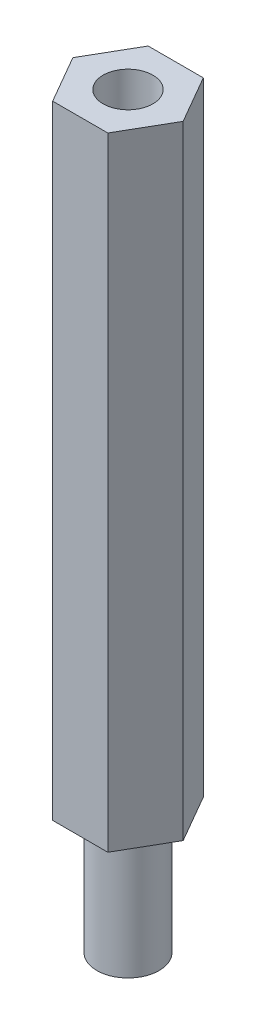
SolidWorks part; units mm, degrees
other "Markup1"
sketch "Sketch2" plane through (2.6558, 40, 2.3) normal (0.3825, 0.9065, 0.1787) x (0.7461, -0.1889, -0.6385)
ref_plane "Front Plane" through (0, 0, 0) normal (0, 0, 1) x (1, 0, 0)
ref_plane "Top Plane" through (0, 0, 0) normal (0, 1, 0) x (1, 0, 0)
ref_plane "Right Plane" through (0, 0, 0) normal (1, 0, 0) x (0, 0, -1)
sketch "Sketch1" plane through (0, 0, 0) normal (0, 1, 0) x (1, 0, 0)
  line L1 (2.6558, 0) -> (1.3279, 2.3)
  line L2 (1.3279, 2.3) -> (-1.3279, 2.3)
  line L3 (-1.3279, 2.3) -> (-2.6558, 0)
  line L4 (-2.6558, 0) -> (-1.3279, -2.3)
  line L5 (-1.3279, -2.3) -> (1.3279, -2.3)
  line L6 (1.3279, -2.3) -> (2.6558, 0)
  circle A0 centre (0, 0) radius 2.3 construction
  circle A2 centre (0, 0) radius 1.2
  dimension "D2" = 1.2
  dimension "D1" = 4.6
extrude "Boss-Extrude1" add sketch "Sketch1" along normal blind 30
sketch "Sketch3" plane through (0, 0, 0) normal (0, -1, 0) x (-1, 0, 0)
  circle A0 centre (0, 0) radius 1.5
  dimension "D1" = 3
extrude "Boss-Extrude2" add sketch "Sketch3" along normal blind 6
